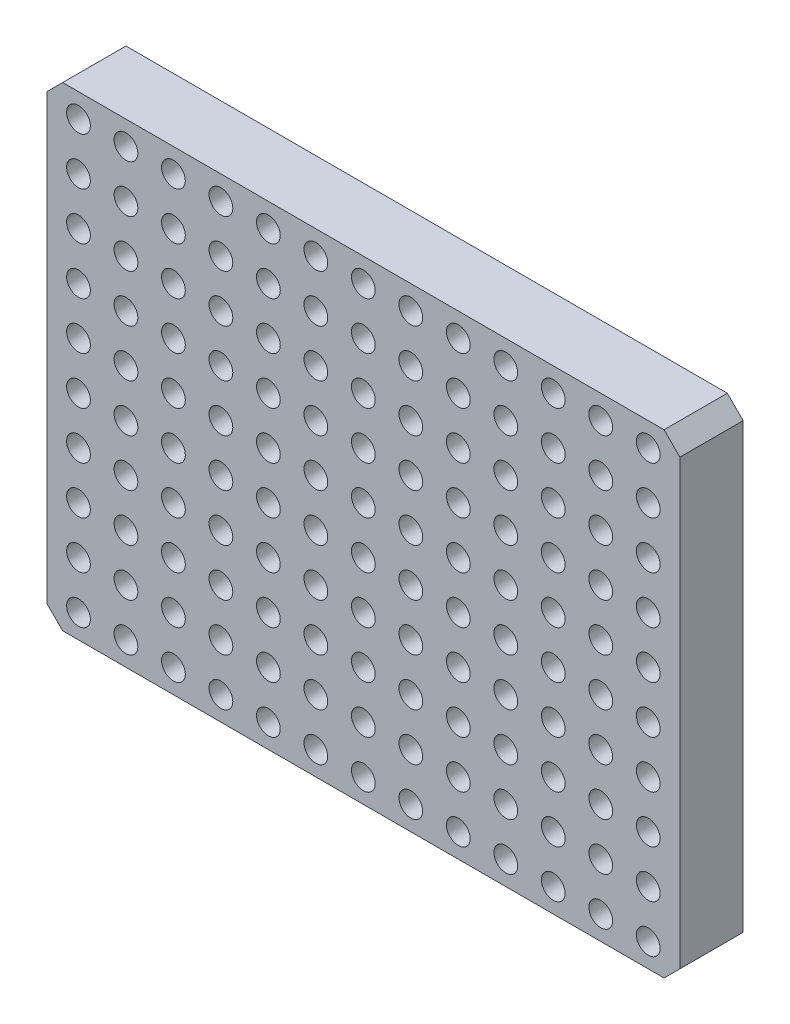
SolidWorks part; units mm, degrees
ref_plane "前视基准面" through (0, 0, 0) normal (0, 0, 1) x (1, 0, 0)
ref_plane "上视基准面" through (0, 0, 0) normal (0, 1, 0) x (1, 0, 0)
ref_plane "右视基准面" through (0, 0, 0) normal (1, 0, 0) x (0, 0, -1)
sketch "草图1" plane through (0, 0, 0) normal (0, 0, 1) x (1, 0, 0)
  line L1 (-200, -150) -> (200, -150)
  line L2 (-200, -150) -> (-200, 150)
  line L3 (-200, 150) -> (200, 150)
  line L4 (200, -150) -> (200, 150)
  line L5 (-200, -150) -> (200, 150) construction
  line L6 (-200, 150) -> (200, -150) construction
  point P0 (0, 0)
  dimension "D1" = 300
  dimension "D2" = 400
extrude "凸台-拉伸1" add sketch "草图1" along normal blind 40
sketch "草图2" plane through (0, 0, 40) normal (0, 0, 1) x (1, 0, 0)
  line L0 (-200, 150) -> (-200, -150) construction
  line L1 (200, 150) -> (-200, 150) construction
  line L2 (-180, 135) -> (-150, 135) construction
  line L3 (-180, 135) -> (-180, 105) construction
  circle A0 centre (-180, 135) radius 7.5
  circle A1 centre (-150, 135) radius 7.5
  circle A2 centre (-120, 135) radius 7.5
  circle A3 centre (-90, 135) radius 7.5
  circle A4 centre (-60, 135) radius 7.5
  circle A5 centre (-30, 135) radius 7.5
  circle A6 centre (0, 135) radius 7.5
  circle A7 centre (30, 135) radius 7.5
  circle A8 centre (60, 135) radius 7.5
  circle A9 centre (90, 135) radius 7.5
  circle A10 centre (120, 135) radius 7.5
  circle A11 centre (150, 135) radius 7.5
  circle A12 centre (180, 135) radius 7.5
  circle A13 centre (-150, 105) radius 7.5
  circle A14 centre (-120, 105) radius 7.5
  circle A15 centre (-90, 105) radius 7.5
  circle A16 centre (-60, 105) radius 7.5
  circle A17 centre (-30, 105) radius 7.5
  circle A18 centre (0, 105) radius 7.5
  circle A19 centre (30, 105) radius 7.5
  circle A20 centre (60, 105) radius 7.5
  circle A21 centre (90, 105) radius 7.5
  circle A22 centre (120, 105) radius 7.5
  circle A23 centre (150, 105) radius 7.5
  circle A24 centre (180, 105) radius 7.5
  circle A25 centre (-150, 75) radius 7.5
  circle A26 centre (-120, 75) radius 7.5
  circle A27 centre (-90, 75) radius 7.5
  circle A28 centre (-60, 75) radius 7.5
  circle A29 centre (-30, 75) radius 7.5
  circle A30 centre (0, 75) radius 7.5
  circle A31 centre (30, 75) radius 7.5
  circle A32 centre (60, 75) radius 7.5
  circle A33 centre (90, 75) radius 7.5
  circle A34 centre (120, 75) radius 7.5
  circle A35 centre (150, 75) radius 7.5
  circle A36 centre (180, 75) radius 7.5
  circle A37 centre (-150, 45) radius 7.5
  circle A38 centre (-120, 45) radius 7.5
  circle A39 centre (-90, 45) radius 7.5
  circle A40 centre (-60, 45) radius 7.5
  circle A41 centre (-30, 45) radius 7.5
  circle A42 centre (0, 45) radius 7.5
  circle A43 centre (30, 45) radius 7.5
  circle A44 centre (60, 45) radius 7.5
  circle A45 centre (90, 45) radius 7.5
  circle A46 centre (120, 45) radius 7.5
  circle A47 centre (150, 45) radius 7.5
  circle A48 centre (180, 45) radius 7.5
  circle A49 centre (-150, 15) radius 7.5
  circle A50 centre (-120, 15) radius 7.5
  circle A51 centre (-90, 15) radius 7.5
  circle A52 centre (-60, 15) radius 7.5
  circle A53 centre (-30, 15) radius 7.5
  circle A54 centre (0, 15) radius 7.5
  circle A55 centre (30, 15) radius 7.5
  circle A56 centre (60, 15) radius 7.5
  circle A57 centre (90, 15) radius 7.5
  circle A58 centre (120, 15) radius 7.5
  circle A59 centre (150, 15) radius 7.5
  circle A60 centre (180, 15) radius 7.5
  circle A61 centre (-150, -15) radius 7.5
  circle A62 centre (-120, -15) radius 7.5
  circle A63 centre (-90, -15) radius 7.5
  circle A64 centre (-60, -15) radius 7.5
  circle A65 centre (-30, -15) radius 7.5
  circle A66 centre (0, -15) radius 7.5
  circle A67 centre (30, -15) radius 7.5
  circle A68 centre (60, -15) radius 7.5
  circle A69 centre (90, -15) radius 7.5
  circle A70 centre (120, -15) radius 7.5
  circle A71 centre (150, -15) radius 7.5
  circle A72 centre (180, -15) radius 7.5
  circle A73 centre (-150, -45) radius 7.5
  circle A74 centre (-120, -45) radius 7.5
  circle A75 centre (-90, -45) radius 7.5
  circle A76 centre (-60, -45) radius 7.5
  circle A77 centre (-30, -45) radius 7.5
  circle A78 centre (0, -45) radius 7.5
  circle A79 centre (30, -45) radius 7.5
  circle A80 centre (60, -45) radius 7.5
  circle A81 centre (90, -45) radius 7.5
  circle A82 centre (120, -45) radius 7.5
  circle A83 centre (150, -45) radius 7.5
  circle A84 centre (180, -45) radius 7.5
  circle A85 centre (-150, -75) radius 7.5
  circle A86 centre (-120, -75) radius 7.5
  circle A87 centre (-90, -75) radius 7.5
  circle A88 centre (-60, -75) radius 7.5
  circle A89 centre (-30, -75) radius 7.5
  circle A90 centre (0, -75) radius 7.5
  circle A91 centre (30, -75) radius 7.5
  circle A92 centre (60, -75) radius 7.5
  circle A93 centre (90, -75) radius 7.5
  circle A94 centre (120, -75) radius 7.5
  circle A95 centre (150, -75) radius 7.5
  circle A96 centre (180, -75) radius 7.5
  circle A97 centre (-150, -105) radius 7.5
  circle A98 centre (-120, -105) radius 7.5
  circle A99 centre (-90, -105) radius 7.5
  circle A100 centre (-60, -105) radius 7.5
  circle A101 centre (-30, -105) radius 7.5
  circle A102 centre (0, -105) radius 7.5
  circle A103 centre (30, -105) radius 7.5
  circle A104 centre (60, -105) radius 7.5
  circle A105 centre (90, -105) radius 7.5
  circle A106 centre (120, -105) radius 7.5
  circle A107 centre (150, -105) radius 7.5
  circle A108 centre (180, -105) radius 7.5
  circle A109 centre (-150, -135) radius 7.5
  circle A110 centre (-120, -135) radius 7.5
  circle A111 centre (-90, -135) radius 7.5
  circle A112 centre (-60, -135) radius 7.5
  circle A113 centre (-30, -135) radius 7.5
  circle A114 centre (0, -135) radius 7.5
  circle A115 centre (30, -135) radius 7.5
  circle A116 centre (60, -135) radius 7.5
  circle A117 centre (90, -135) radius 7.5
  circle A118 centre (120, -135) radius 7.5
  circle A119 centre (150, -135) radius 7.5
  circle A120 centre (180, -135) radius 7.5
  circle A121 centre (-180, 105) radius 7.5
  circle A122 centre (-180, 75) radius 7.5
  circle A123 centre (-180, 45) radius 7.5
  circle A124 centre (-180, 15) radius 7.5
  circle A125 centre (-180, -15) radius 7.5
  circle A126 centre (-180, -45) radius 7.5
  circle A127 centre (-180, -75) radius 7.5
  circle A128 centre (-180, -105) radius 7.5
  circle A129 centre (-180, -135) radius 7.5
  dimension "D1" = 15
  dimension "D2" = 20
  dimension "D3" = 15
  dimension "D7" = 30
  dimension "D6" = 30
  dimension "D4" = 13
  dimension "D5" = 10
extrude "切除-拉伸1" cut sketch "草图2" against normal blind 20
chamfer "倒角1" distance 10 angle 45 4 edges at (-200, -150, 20) (200, -150, 20) (200, 150, 20) (-200, 150, 20)
